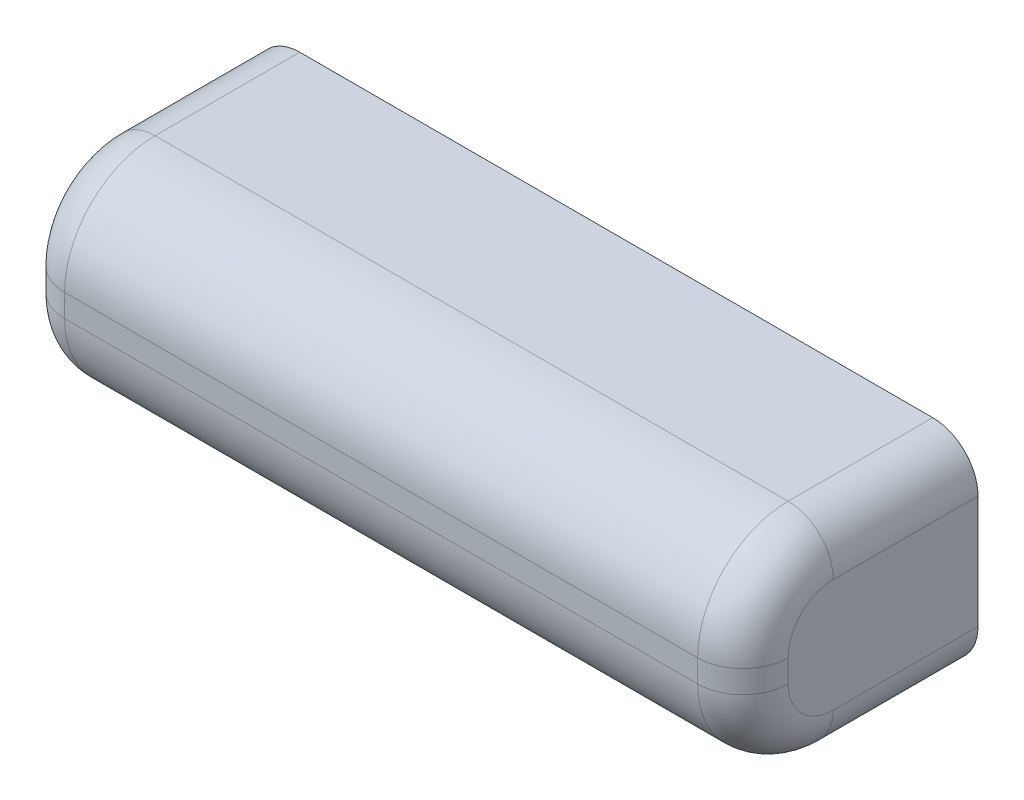
SolidWorks part; units mm, degrees
ref_plane "정면" through (0, 0, 0) normal (0, 0, 1) x (1, 0, 0)
ref_plane "윗면" through (0, 0, 0) normal (0, 1, 0) x (1, 0, 0)
ref_plane "우측면" through (0, 0, 0) normal (1, 0, 0) x (0, 0, -1)
sketch "스케치1" plane through (0, 0, 0) normal (0, 0, 1) x (1, 0, 0)
  line L1 (-80, 22.5) -> (80, 22.5)
  line L2 (-80, 22.5) -> (-80, -22.5)
  line L3 (-80, -22.5) -> (80, -22.5)
  line L4 (80, 22.5) -> (80, -22.5)
  line L5 (-80, 22.5) -> (80, -22.5) construction
  line L6 (-80, -22.5) -> (80, 22.5) construction
  point P0 (0, 0)
  dimension "D1" = 160
  dimension "D2" = 45
extrude "보스-돌출1" add sketch "스케치1" along normal blind 52
sketch "스케치2" plane through (0, 0, 0) normal (0, 0, -1) x (-1, 0, 0)
  circle A1 centre (0, 0) radius 15
  dimension "D1" = 30
extrude "컷-돌출1" cut sketch "스케치2" against normal blind 10
pattern_linear "선형 패턴2" count 3 spacing 32 along (-1, 0, 0) of "컷-돌출1"
pattern_linear "선형 패턴3" count 3 spacing 32 along (1, 0, 0) of "컷-돌출1"
fillet "필렛1" radius 20 2 edges at (0, -22.5, 52) (0, 22.5, 52)
fillet "필렛2" radius 10 10 edges at (-80, -22.5, 16) (-80, -16.6421, 46.1421) (-80, 0, 52) (-80, 16.6421, 46.1421) (80, -22.5, 16) (80, -16.6421, 46.1421) (80, 0, 52) (80, 16.6421, 46.1421) (-80, 22.5, 16) (80, 22.5, 16)
